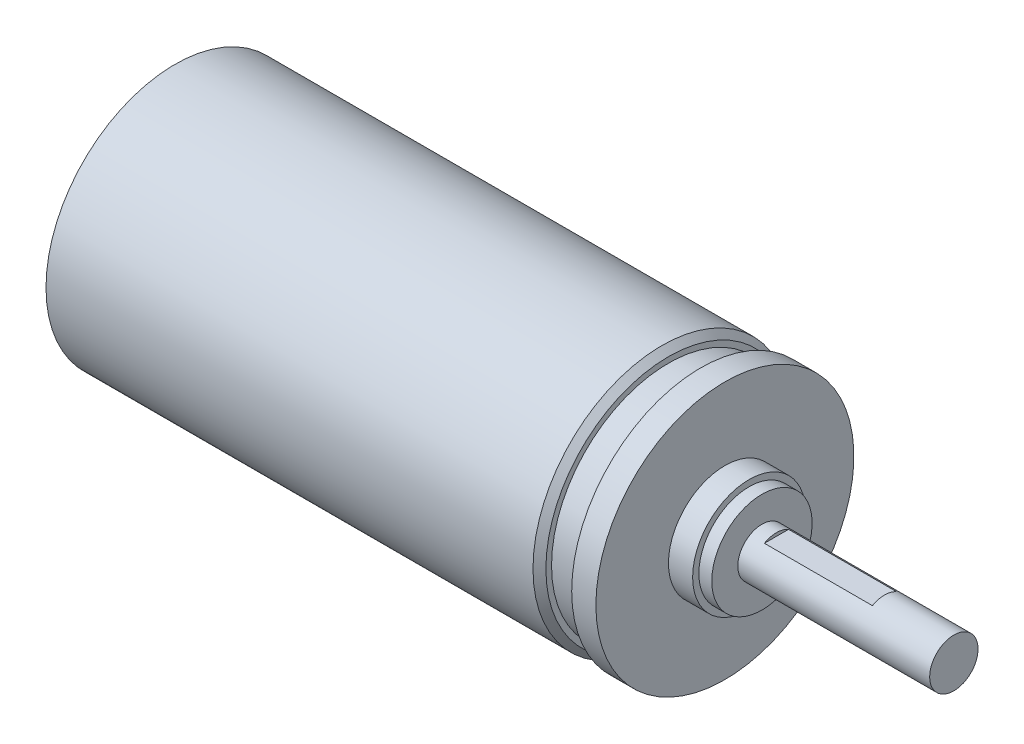
SolidWorks part; units mm, degrees
ref_plane "Plan de face" through (0, 0, 0) normal (0, 0, 1) x (1, 0, 0)
ref_plane "Plan de dessus" through (0, 0, 0) normal (0, 1, 0) x (1, 0, 0)
ref_plane "Plan de droite" through (0, 0, 0) normal (1, 0, 0) x (0, 0, -1)
sketch "Esquisse1" plane through (0, 0, 0) normal (0, 0, 1) x (1, 0, 0)
  line L0 (-64.66, 0) -> (70.5748, 0) construction
  line L1 (-22.2722, 0) -> (-22.2722, 8)
  line L2 (-22.2722, 8) -> (8.3278, 8)
  line L3 (8.3278, 8) -> (8.3278, 7.25)
  line L4 (8.3278, 7.25) -> (10.3278, 7.25)
  line L5 (10.3278, 7.25) -> (10.3278, 8)
  line L6 (10.3278, 8) -> (11.8278, 8)
  line L7 (11.8278, 8) -> (11.8278, 3.5)
  line L8 (11.8278, 3.5) -> (13.3278, 3.5)
  line L9 (13.3278, 3.5) -> (13.3278, 3.1117)
  line L10 (13.3278, 3.1117) -> (14.1278, 3.1117)
  line L11 (14.1278, 3.1117) -> (14.1278, 1.5)
  line L12 (14.1278, 1.5) -> (26.0278, 1.5)
  line L13 (26.0278, 1.5) -> (26.0278, 0)
  line L14 (26.0278, 0) -> (-22.2722, 0)
  dimension "D1" = 8
  dimension "D2" = 7.25
  dimension "D3" = 8
  dimension "D4" = 2
  dimension "D5" = 34.1
  dimension "D6" = 1.5
  dimension "D7" = 3.5
  dimension "D8" = 1.5
  dimension "D9" = 0.8
  dimension "D10" = 11.9
  dimension "D11" = 1.5
revolve "Révolution1" add sketch "Esquisse1" angle 360 about L0
chamfer "Chanfrein1" distance 0.4 angle 45 1 edges at (8.3278, 0, 8)
sketch "Esquisse2" plane through (0, 0, 0) normal (0, 0, 1) x (1, 0, 0)
  line L0 (21.7278, 1.5) -> (21.7278, 1.3)
  line L1 (26.0278, 1.5) -> (14.1278, 1.5) construction
  line L2 (21.7278, 1.3) -> (15.0278, 1.3)
  line L3 (15.0278, 1.3) -> (15.0278, 1.5)
  line L4 (15.0278, 1.5) -> (21.7278, 1.5)
  line L5 (26.0278, -1.5) -> (26.0278, 1.5) construction
  dimension "D1" = 4.3
  dimension "D2" = 0.2
  dimension "D3" = 6.7
extrude "Extrusion1" cut sketch "Esquisse2" against normal through all and the other way through all
